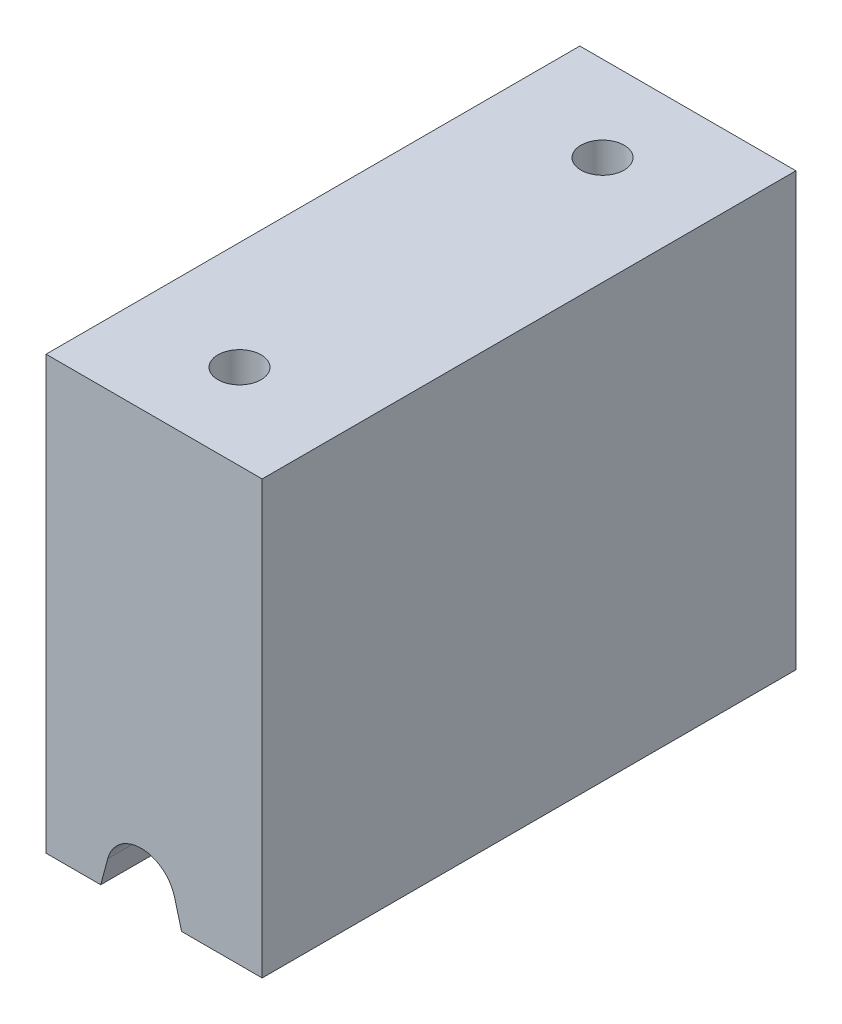
SolidWorks part; units mm, degrees
material "K110"
ref_plane "Front Plane" through (0, 0, 0) normal (0, 0, 1) x (1, 0, 0)
ref_plane "Top Plane" through (0, 0, 0) normal (0, 1, 0) x (1, 0, 0)
ref_plane "Right Plane" through (0, 0, 0) normal (1, 0, 0) x (0, 0, -1)
sketch "Sketch1" plane through (0, 0, 0) normal (0, 0, 1) x (1, 0, 0)
  line L1 (-12.5, -50) -> (12.5, -50)
  line L2 (-12.5, -50) -> (-12.5, 0)
  line L3 (-12.5, 0) -> (12.5, 0)
  line L4 (12.5, -50) -> (12.5, 0)
  point P4 (0, 0)
  dimension "D1" = 25
  dimension "D2" = 50
extrude "Boss-Extrude1" add sketch "Sketch1" along normal mid plane 61.75
sketch "Sketch2" plane through (0, 0, -30.875) normal (0, 0, -1) x (-1, 0, 0)
  line L0 (-2.3637, -46.9647) -> (-3.177, -50)
  line L1 (12.5, -50) -> (-12.5, -50) construction
  line L2 (-2.3637, -46.9647) -> (-2.3637, -50) construction
  line L3 (1.5, -48) -> (1.5, -44) construction
  line L4 (5.3637, -46.9647) -> (6.177, -50)
  line L5 (-3.177, -50) -> (6.177, -50)
  line L6 (-12.5, -50) -> (-12.5, 0) construction
  line L7 (5.3637, -46.9647) -> (5.3637, -50) construction
  arc A1 (5.3637, -46.9647) -> (-2.3637, -46.9647) centre (1.5, -48) ccw
  dimension "D2" = 4
  dimension "D1" = 15
  dimension "D3" = 2
  dimension "D4" = 14
  dimension "D5" = 15
extrude "Cut-Extrude1" cut sketch "Sketch2" against normal up to next
hole_wizard "M6 Tapped Hole1" positions "Sketch6" profile "Sketch4" tap size "M6" standard "ISO"
sketch "Sketch6" plane through (0, 0, 0) normal (0, 1, 0) x (1, 0, 0)
  line L0 (0, 30.875) -> (0, -30.875) construction
  line L1 (12.5, 30.875) -> (-12.5, 30.875) construction
  line L2 (12.5, -30.875) -> (-12.5, -30.875) construction
  line L4 (-12.5, 0) -> (12.5, 0) construction
  line L5 (-12.5, -30.875) -> (-12.5, 30.875) construction
  line L6 (12.5, -30.875) -> (12.5, 30.875) construction
  point P0 (0, 21)
  point P2 (0, -21)
  dimension "D1" = 42
cosmetic thread "Hole Thread1"
cosmetic thread "Hole Thread2"
sketch "Sketch4" plane through (0, 0, -21) normal (1, 0, 0) x (0, 0, 1)
  line L0 (0, 0) -> (0, 18.5022)
  line L1 (0, 18.5022) -> (2.5, 17)
  line L2 (2.5, 17) -> (2.5, 0)
  line L5 (2.5, 0) -> (0, 0)
  line L10 (0, 18.5022) -> (-2.5, 17) construction
  line L11 (0, -6.35) -> (0, 107.95) construction
  dimension "Tap Drill Dia." = 5
  dimension "Tap Drill Depth" = 17
  dimension "Drill Angle" = 118
